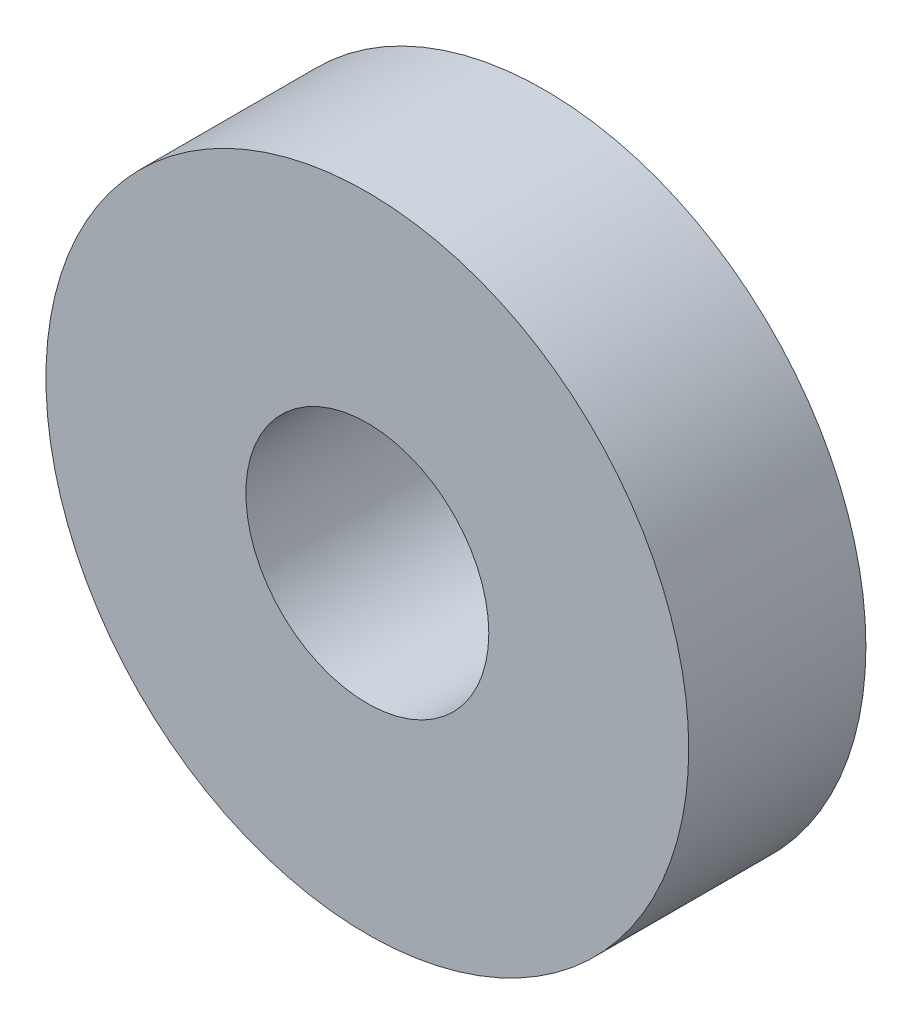
SolidWorks part; units mm, degrees
ref_plane "Front" through (0, 0, 0) normal (0, 0, 1) x (1, 0, 0)
ref_plane "Top" through (0, 0, 0) normal (0, 1, 0) x (1, 0, 0)
ref_plane "Right" through (0, 0, 0) normal (1, 0, 0) x (0, 0, -1)
sketch "Sketch1" plane through (0, 0, 0) normal (0, 0, 1) x (1, 0, 0)
  circle A0 centre (0, 0) radius 12.7
  circle A1 centre (0, 0) radius 4.8
  dimension "D1" = 25.4
  dimension "D2" = 9.6
extrude "Boss-Extrude1" add sketch "Sketch1" along normal blind 7
